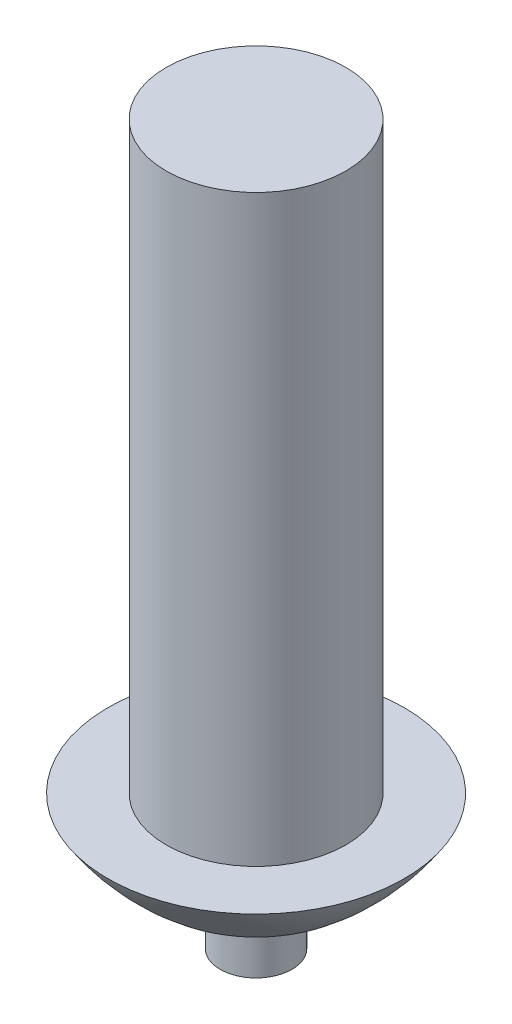
SolidWorks part; units mm, degrees
ref_plane "Front" through (0, 0, 0) normal (0, 0, 1) x (1, 0, 0)
ref_plane "Top" through (0, 0, 0) normal (0, 1, 0) x (1, 0, 0)
ref_plane "Right" through (0, 0, 0) normal (1, 0, 0) x (0, 0, -1)
sketch "Sketch1" plane through (0, 0, 0) normal (1, 0, 0) x (0, 0, -1)
  line L0 (0, 0) -> (0, 8.5488) construction
  line L1 (0, 6.5) -> (0, -1.5)
  line L2 (0, -1.5) -> (0.4, -1.5)
  line L3 (0.4, -1.5) -> (0.4, -1)
  line L4 (0, 6.5) -> (1, 6.5)
  line L5 (1, 6.5) -> (1, 0)
  line L6 (1, 0) -> (1.65, 0)
  line L7 (0, 0) -> (4.4514, 0) construction
  arc A0 (1.65, 0) -> (0.4, -1) centre (-0.4545, 1.3494) cw
  dimension "D7" = 2.5
  dimension "D1" = 6.5
  dimension "D2" = 2
  dimension "D3" = 3.3
  dimension "D4" = 0.8
  dimension "D5" = 1.5
  dimension "D6" = 1
revolve "Revolve1" add sketch "Sketch1" angle 360 about L0
